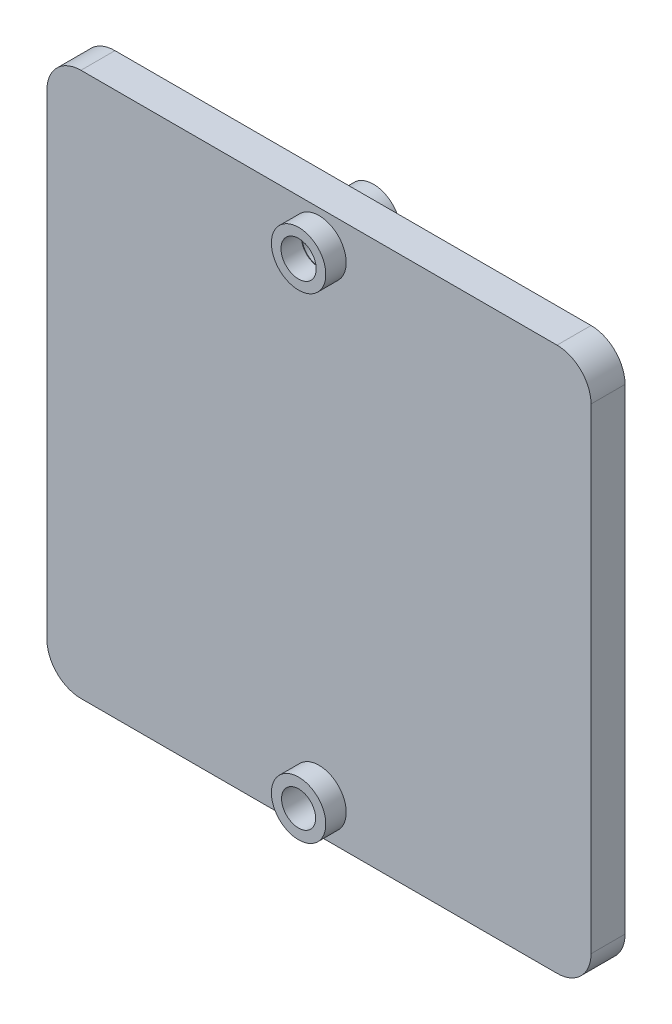
SolidWorks part; units mm, degrees
ref_plane "Front Plane" through (0, 0, 0) normal (0, 0, 1) x (1, 0, 0)
ref_plane "Top Plane" through (0, 0, 0) normal (0, 1, 0) x (1, 0, 0)
ref_plane "Right Plane" through (0, 0, 0) normal (1, 0, 0) x (0, 0, -1)
sketch "Sketch1" plane through (0, 0, 0) normal (0, 0, 1) x (1, 0, 0)
  line L1 (0, 0) -> (400, 0)
  line L2 (0, 0) -> (0, -400)
  line L3 (0, -400) -> (400, -400)
  line L4 (400, 0) -> (400, -400)
  dimension "D1" = 400
  dimension "D2" = 400
extrude "Boss-Extrude1" add sketch "Sketch1" along normal blind 25
fillet "Fillet1" radius 25 4 edges at (0, -400, 12.5) (400, -400, 12.5) (400, 0, 12.5) (0, 0, 12.5)
sketch "Sketch2" plane through (0, 0, 0) normal (0, 0, -1) x (-1, 0, 0)
  line L0 (-375, 0) -> (-25, 0) construction
  line L1 (-25, -400) -> (-375, -400) construction
  circle A0 centre (-200, -25) radius 12.5
  circle A1 centre (-200, -375) radius 12.5
  dimension "D1" = 25
  dimension "D2" = 25
  dimension "D3" = 25
  dimension "D4" = 25
extrude "Cut-Extrude1" cut sketch "Sketch2" against normal blind 25 contours A0 | A1
sketch "Sketch3" plane through (0, 0, 0) normal (0, 0, -1) x (-1, 0, 0)
  circle A0 centre (-200, -25) radius 12.9577
  circle A1 centre (-200, -25) radius 20
  circle A2 centre (-200, -375) radius 12.5
  circle A3 centre (-200, -375) radius 20
extrude "Boss-Extrude2" add sketch "Sketch3" along normal blind 15 and the other way blind 40
